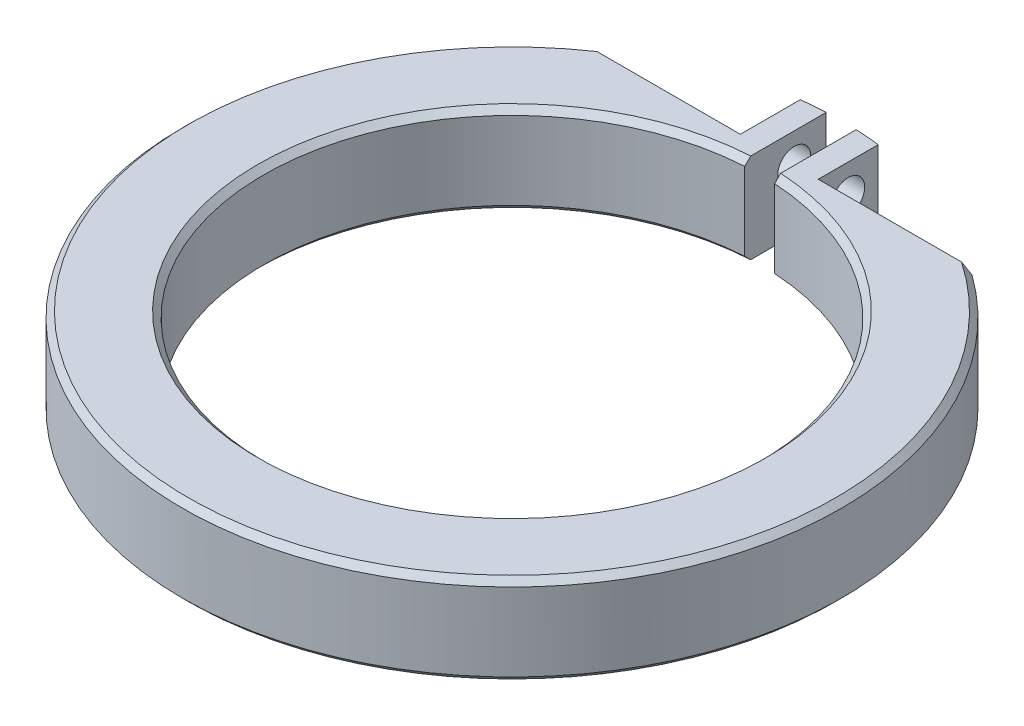
SolidWorks part; units mm, degrees
material "1.0037 (S235JR)"
ref_plane "Front Plane" through (0, 0, 0) normal (0, 0, 1) x (1, 0, 0)
ref_plane "Top Plane" through (0, 0, 0) normal (0, 1, 0) x (1, 0, 0)
ref_plane "Right Plane" through (0, 0, 0) normal (1, 0, 0) x (0, 0, -1)
sketch "Sketch1" plane through (0, 0, 0) normal (0, 1, 0) x (1, 0, 0)
  circle A0 centre (0, 0) radius 41.4175
  circle A1 centre (0, 0) radius 55
  dimension "D1" = 82.835
  dimension "D2" = 110
extrude "Boss-Extrude1" add sketch "Sketch1" along normal blind 15
sketch "Sketch2" plane through (0, 15, 0) normal (0, 1, 0) x (1, 0, 0)
  line L0 (0, -1000) -> (0, 49000) construction
  line L1 (-2.5, 41.342) -> (-2.5, 54.9432)
  line L2 (2.5, 41.342) -> (2.5, 54.9432)
  circle A0 centre (0, 0) radius 41.4175 construction
  circle A1 centre (0, 0) radius 55 construction
  arc A2 (2.5, 41.342) -> (-2.5, 41.342) centre (0, 0) ccw
  arc A3 (2.5, 54.9432) -> (-2.5, 54.9432) centre (0, 0) ccw
  dimension "D1" = 5
extrude "Cut-Extrude1" cut sketch "Sketch2" against normal through all
sketch "Sketch3" plane through (0, 15, 0) normal (0, 1, 0) x (1, 0, 0)
  line L0 (-6.5, 54.6146) -> (-6.5, 44.6146)
  line L1 (-6.5, 44.6146) -> (-32.1643, 44.6146)
  line L3 (-2.5, 54.9432) -> (-2.5, 41.342) construction
  line L4 (0, -1000) -> (0, 49000) construction
  line L5 (6.5, 44.6146) -> (32.1643, 44.6146)
  line L6 (6.5, 54.6146) -> (6.5, 44.6146)
  arc A0 (-2.5, 54.9432) -> (2.5, 54.9432) centre (0, 0) ccw construction
  arc A1 (-6.5, 54.6146) -> (-32.1643, 44.6146) centre (0, 0) ccw
  arc A3 (6.5, 54.6146) -> (32.1643, 44.6146) centre (0, 0) cw
  dimension "D1" = 10
  dimension "D2" = 4
extrude "Cut-Extrude2" cut sketch "Sketch3" against normal blind 10
sketch "Sketch4" plane through (-6.5, 0, 0) normal (-1, 0, 0) x (0, 0, 1)
  line L0 (-44.6146, 15) -> (-54.6146, 15) construction
  line L1 (-54.6146, 5) -> (-54.6146, 15) construction
  circle A0 centre (-49.6146, 10) radius 2.75
  point P2 (-49.6146, 15)
  point P6 (-54.6146, 10)
  dimension "D1" = 5.5
extrude "Cut-Extrude3" cut sketch "Sketch4" against normal through all
fillet "Fillet2" radius 2 2 edges at (-19.3321, 5, -44.6146) (19.3321, 5, -44.6146)
chamfer "Chamfer2" distance 1 angle 45 2 edges at (0, 15, 55) (0, 0, 55)
chamfer "Chamfer3" distance 1 angle 45 2 edges at (0, 0, 41.4175) (0, 15, 41.4175)
